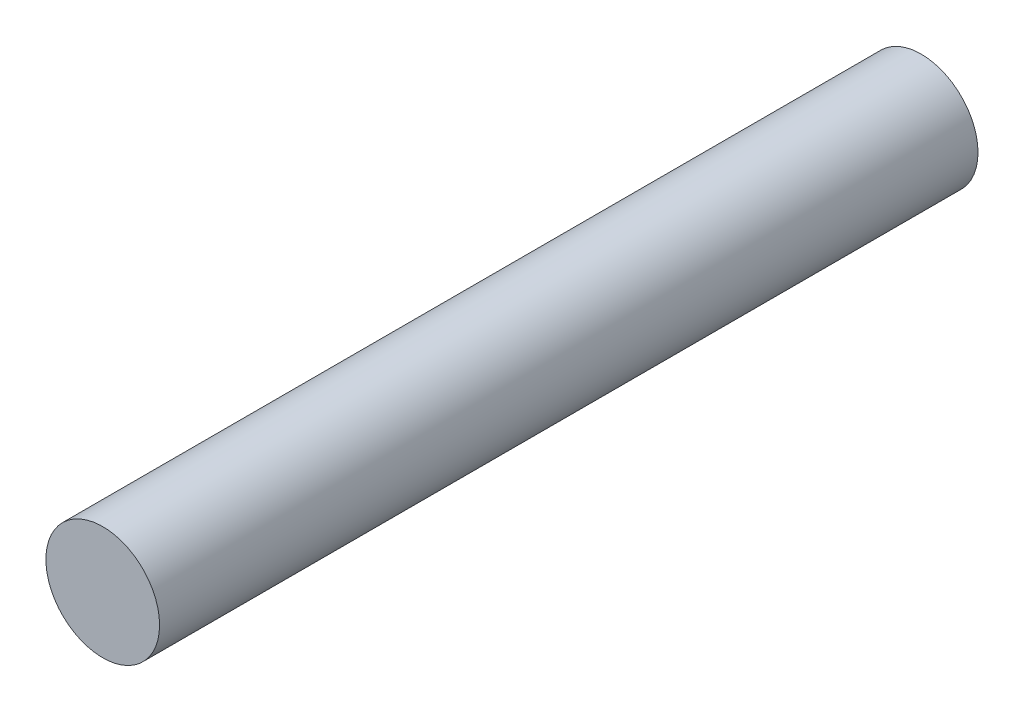
SolidWorks part; units mm, degrees
ref_plane "前视基准面" through (0, 0, 0) normal (0, 0, 1) x (1, 0, 0)
ref_plane "上视基准面" through (0, 0, 0) normal (0, 1, 0) x (1, 0, 0)
ref_plane "右视基准面" through (0, 0, 0) normal (1, 0, 0) x (0, 0, -1)
sketch "草图1" plane through (0, 0, 0) normal (0, 0, 1) x (1, 0, 0)
  circle A0 centre (0, 0) radius 5
  dimension "D1" = 10
extrude "凸台-拉伸1" add sketch "草图1" along normal blind 72
